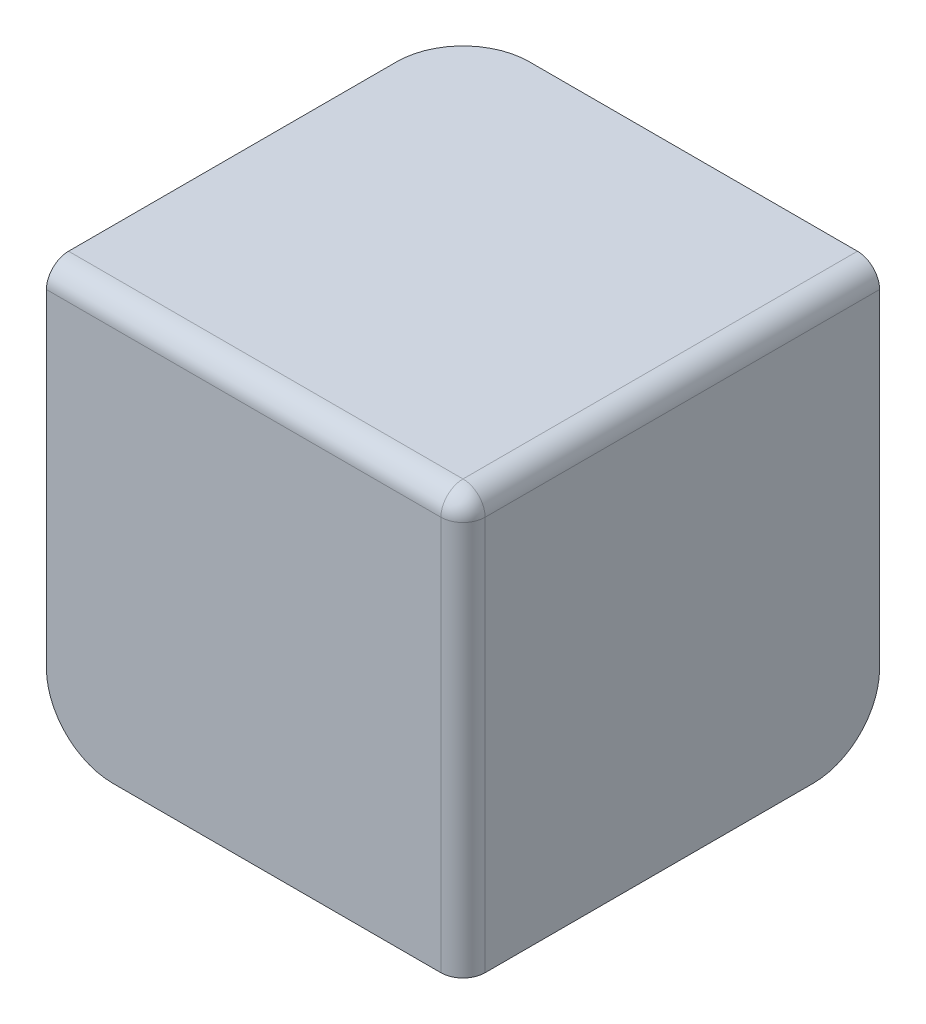
SolidWorks part; units mm, degrees
ref_plane "前视基准面" through (0, 0, 0) normal (0, 0, 1) x (1, 0, 0)
ref_plane "上视基准面" through (0, 0, 0) normal (0, 1, 0) x (1, 0, 0)
ref_plane "右视基准面" through (0, 0, 0) normal (1, 0, 0) x (0, 0, -1)
sketch "草图1" plane through (0, 0, 0) normal (0, 1, 0) x (1, 0, 0)
  line L1 (-9.42, -9.42) -> (9.42, -9.42)
  line L2 (-9.42, -9.42) -> (-9.42, 9.42)
  line L3 (-9.42, 9.42) -> (9.42, 9.42)
  line L4 (9.42, -9.42) -> (9.42, 9.42)
  line L5 (0, 9.42) -> (0, -9.42) construction
  line L6 (-9.42, 0) -> (9.42, 0) construction
  point P0 (0, 0)
  dimension "D1" = 18.84
  dimension "D2" = 18.84
extrude "凸台-拉伸1" add sketch "草图1" along normal blind 18.84
fillet "圆角1" radius 1 3 edges at (9.42, 9.42, 9.42) (9.42, 18.84, 0) (0, 18.84, 9.42)
fillet "圆角2" radius 3 3 edges at (-9.42, 0, 0) (-9.42, 9.42, -9.42) (0, 0, -9.42)
